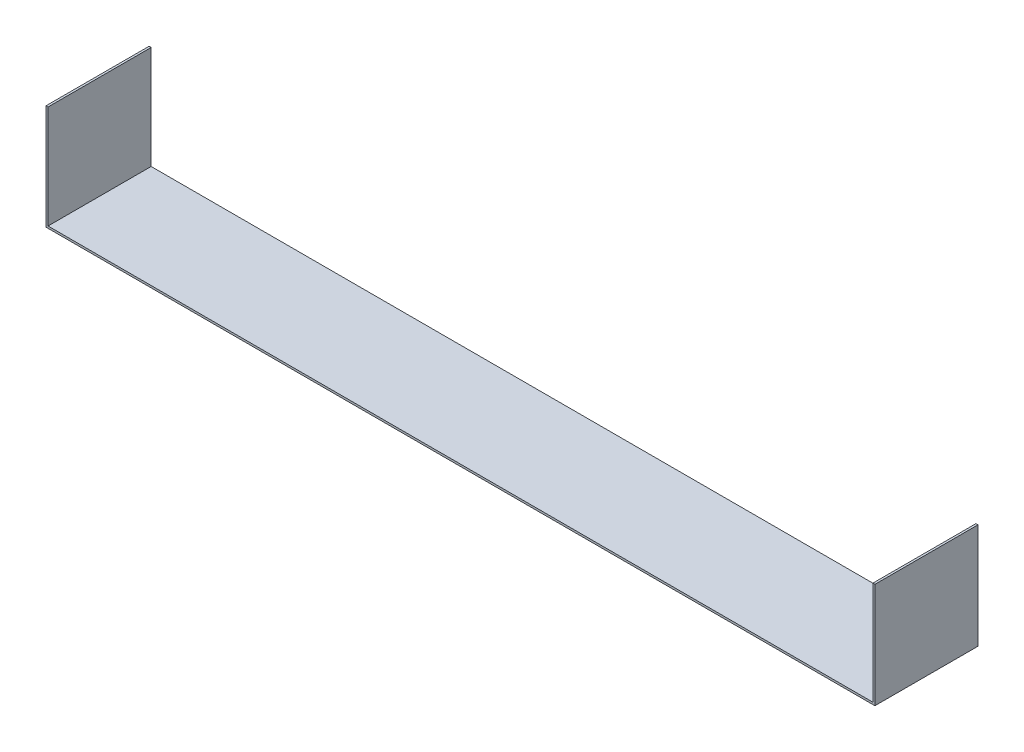
SolidWorks part; units mm, degrees
ref_plane "Front Plane" through (0, 0, 0) normal (0, 0, 1) x (1, 0, 0)
ref_plane "Top Plane" through (0, 0, 0) normal (0, 1, 0) x (1, 0, 0)
ref_plane "Right Plane" through (0, 0, 0) normal (1, 0, 0) x (0, 0, -1)
sketch "Sketch2" plane through (0, 0, 0) normal (0, 0, 1) x (1, 0, 0)
  line L0 (0, 0) -> (0, -10000)
  line L1 (0, -10000) -> (80000, -10000)
  line L2 (80000, -10000) -> (80000, 0)
  line L3 (-200, 0) -> (-200, -10200)
  line L4 (-200, -10200) -> (80200, -10200)
  line L5 (80200, -10200) -> (80200, 0)
  line L6 (-200, 0) -> (0, 0)
  line L7 (80000, 0) -> (80200, 0)
extrude "Boss-Extrude1" add sketch "Sketch2" against normal blind 10000
